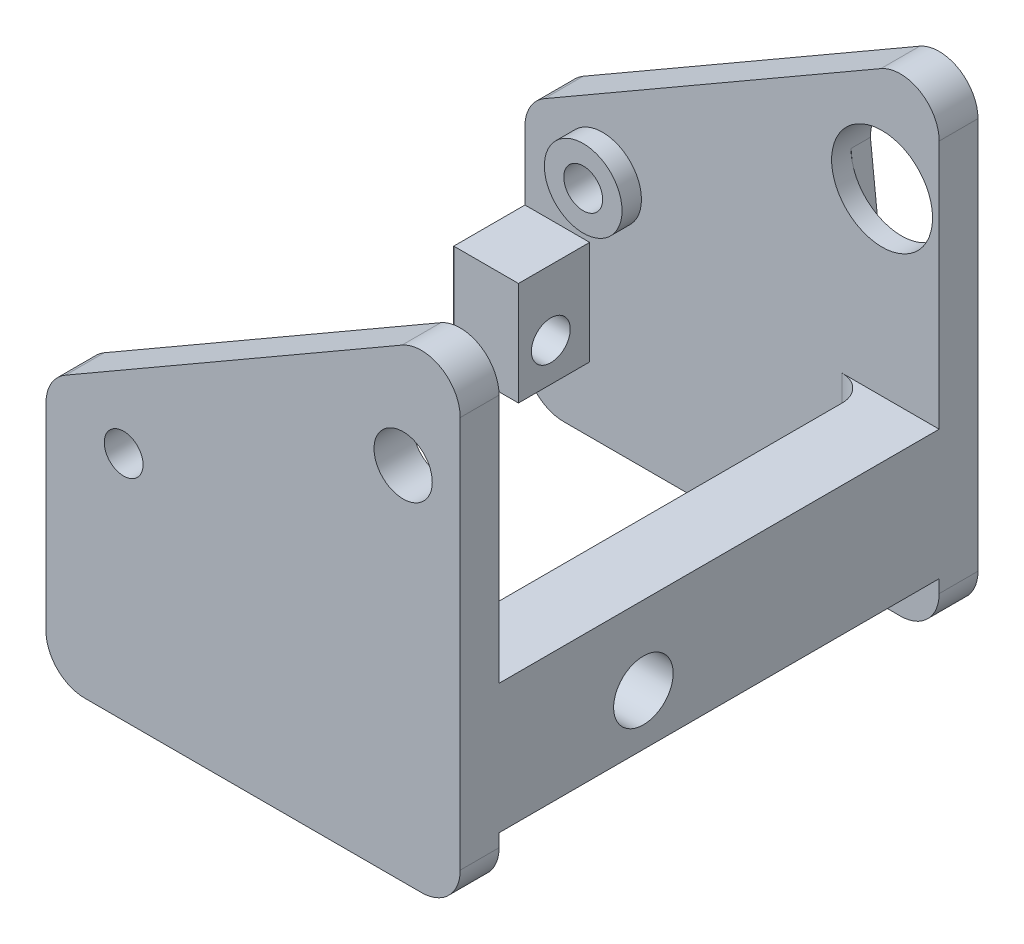
SolidWorks part; units mm, degrees
ref_plane "Front Plane" through (0, 0, 0) normal (0, 0, 1) x (1, 0, 0)
ref_plane "Top Plane" through (0, 0, 0) normal (0, 1, 0) x (1, 0, 0)
ref_plane "Right Plane" through (0, 0, 0) normal (1, 0, 0) x (0, 0, -1)
sketch "Sketch1" plane through (0, 0, 0) normal (0, 0, 1) x (1, 0, 0)
  line L0 (-4.5, -2.5981) -> (-30.5, -17.6092)
  line L1 (-32, -20.2073) -> (-32, -35.4752)
  line L2 (-29, -38.4752) -> (-3, -38.4752)
  line L3 (0, -35.4752) -> (0, -5.1962)
  arc A0 (-3, -38.4752) -> (0, -35.4752) centre (-3, -35.4752) ccw
  arc A1 (-32, -35.4752) -> (-29, -38.4752) centre (-29, -35.4752) ccw
  arc A2 (-30.5, -17.6092) -> (-32, -20.2073) centre (-29, -20.2073) ccw
  arc A3 (-4.5, -2.5981) -> (0, -5.1962) centre (-3, -5.1962) cw
  circle A4 centre (-26, -20.6092) radius 1.5
  circle A5 centre (-4.41, -10.5981) radius 1.5
  point P7 (0, -38.4752)
  point P10 (-32, -38.4752)
  point P13 (-32, -18.4752)
  point P16 (0, 0)
  dimension "D4" = 3
  dimension "D5" = 3
  dimension "D6" = 3
  dimension "D1" = 20
  dimension "D2" = 32
  dimension "D3" = 60
  dimension "D7" = 8
  dimension "D8" = 4.41
  dimension "D9" = 3
  dimension "D10" = 6
extrude "Boss-Extrude1" add sketch "Sketch1" along normal blind 3
sketch "Sketch2" plane through (0, 0, 3) normal (0, 0, 1) x (1, 0, 0)
  line L0 (-32, -20.2073) -> (-32, -35.4752) construction
  line L1 (-32, -25.4752) -> (-27, -25.4752)
  line L2 (-32, -25.4752) -> (-32, -33.4752)
  line L3 (-32, -33.4752) -> (-27, -33.4752)
  line L4 (-27, -25.4752) -> (-27, -33.4752)
  line L5 (-29, -38.4752) -> (-3, -38.4752) construction
  dimension "D1" = 5
  dimension "D2" = 8
  dimension "D3" = 5
extrude "Boss-Extrude2" add sketch "Sketch2" along normal blind 34
sketch "Sketch3" plane through (0, 0, 3) normal (0, 0, 1) x (1, 0, 0)
  line L0 (0, -35.4752) -> (0, -5.1962) construction
  line L1 (0, -24.4752) -> (-5.5, -24.4752)
  line L2 (0, -24.4752) -> (0, -34.4752)
  line L3 (0, -34.4752) -> (-5.5, -34.4752)
  line L4 (-5.5, -24.4752) -> (-5.5, -34.4752)
  line L5 (-29, -38.4752) -> (-3, -38.4752) construction
  dimension "D1" = 5.5
  dimension "D2" = 10
  dimension "D3" = 4
pattern_linear "LPattern1" count 2 spacing 37 along (0, 0, 1) of "Boss-Extrude1"
extrude "Boss-Extrude4" add sketch "Sketch3" along normal blind 34
sketch "Sketch5" plane through (-32, 0, 0) normal (-1, 0, 0) x (0, 0, 1)
  line L0 (37, -33.4752) -> (3, -33.4752) construction
  line L1 (3, -25.4752) -> (8.5, -25.4752)
  line L2 (3, -25.4752) -> (3, -33.4752)
  line L3 (3, -33.4752) -> (8.5, -33.4752)
  line L4 (8.5, -25.4752) -> (8.5, -33.4752)
  line L5 (8.5, -25.4752) -> (31.5, -25.4752)
  line L6 (37, -25.4752) -> (31.5, -25.4752)
  line L7 (37, -25.4752) -> (37, -33.4752)
  line L8 (37, -33.4752) -> (31.5, -33.4752)
  line L9 (31.5, -25.4752) -> (31.5, -33.4752)
  line L10 (31.5, -33.4752) -> (8.5, -33.4752)
  line M6 (3, -33.4752) -> (37, -33.4752)
  line M12 (37, -25.4752) -> (3, -25.4752)
  dimension "D1" = 5.5
  dimension "D2" = 5.5
extrude "Cut-Extrude1" cut sketch "Sketch5" against normal blind 10 contours L9 L4 M12 M6
sketch "Sketch9" plane through (0, 0, 3) normal (0, 0, 1) x (1, 0, 0)
  line L17 (-6.51, -27.3981) -> (-8.31, -10.5981)
  line L18 (-0.51, -10.5981) -> (-2.31, -27.3981)
  arc A8 (-0.5985, -11.4243) -> (-8.2215, -11.4243) centre (-4.41, -10.5981) ccw
  circle A9 centre (-4.41, -10.5981) radius 1.5 construction
  arc A10 (-6.51, -27.3981) -> (-2.31, -27.3981) centre (-4.41, -27.3981) ccw
  circle M29 centre (-4.41, -10.5981) radius 1.5
  line M30 (-5.5, -34.4752) -> (-5.5, -24.4752)
  line M31 (-5.5, -24.4752) -> (0, -24.4752)
  dimension "D1" = 7.8
  dimension "D2" = 4.2
  dimension "D3" = 16.8
extrude "Cut-Extrude11" cut sketch "Sketch9" against normal blind 2.2 from offset 1.5 contours L17 A10 L18 A8 M30 M31 M29 | A10 L18 M30 M31 offset against normal yes
sketch "Sketch11" plane through (0, 0, 3) normal (0, 0, 1) x (1, 0, 0)
  circle A0 centre (-26, -20.6092) radius 1.5
  circle A1 centre (-26, -20.6092) radius 3
  dimension "D1" = 6
  dimension "D2" = 3
extrude "Boss-Extrude5" add sketch "Sketch11" along normal blind 1.5
sketch "Sketch12" plane through (-27, 0, 0) normal (1, 0, 0) x (0, 0, -1)
  line L0 (-37, -25.4752) -> (-31.5, -25.4752) construction
  line L1 (-31.5, -25.4752) -> (-31.5, -33.4752) construction
  circle A0 centre (-34.4, -30.5252) radius 1.5
  circle A1 centre (-6, -30.5252) radius 1.5
  dimension "D1" = 3
  dimension "D2" = 3
  dimension "D3" = 25.5
  dimension "D4" = 2.9
  dimension "D5" = 5.05
  dimension "D6" = 5.05
extrude "Cut-Extrude13" cut sketch "Sketch12" against normal through all
sketch "Sketch14" plane through (0, 0, 1.5) normal (0, 0, -1) x (-1, 0, 0)
  circle A0 centre (4.41, -10.5981) radius 3.9
extrude "Cut-Extrude15" cut sketch "Sketch14" against normal blind 10
sketch "Sketch15" plane through (0, 0, 0) normal (1, 0, 0) x (0, 0, -1)
  circle A0 centre (-25.85, -30.5252) radius 2.3
  dimension "D1" = 4.6
extrude "Cut-Extrude16" cut sketch "Sketch15" against normal through all
sketch "Sketch16" plane through (0, 0, 40) normal (0, 0, 1) x (1, 0, 0)
  circle A0 centre (-4.41, -10.5981) radius 2.25
  dimension "D1" = 4.5
extrude "Cut-Extrude17" cut sketch "Sketch16" against normal through all
fillet "Fillet1" radius 2 2 edges at (-5.5, -29.4752, 3) (-5.5, -29.4752, 37)
